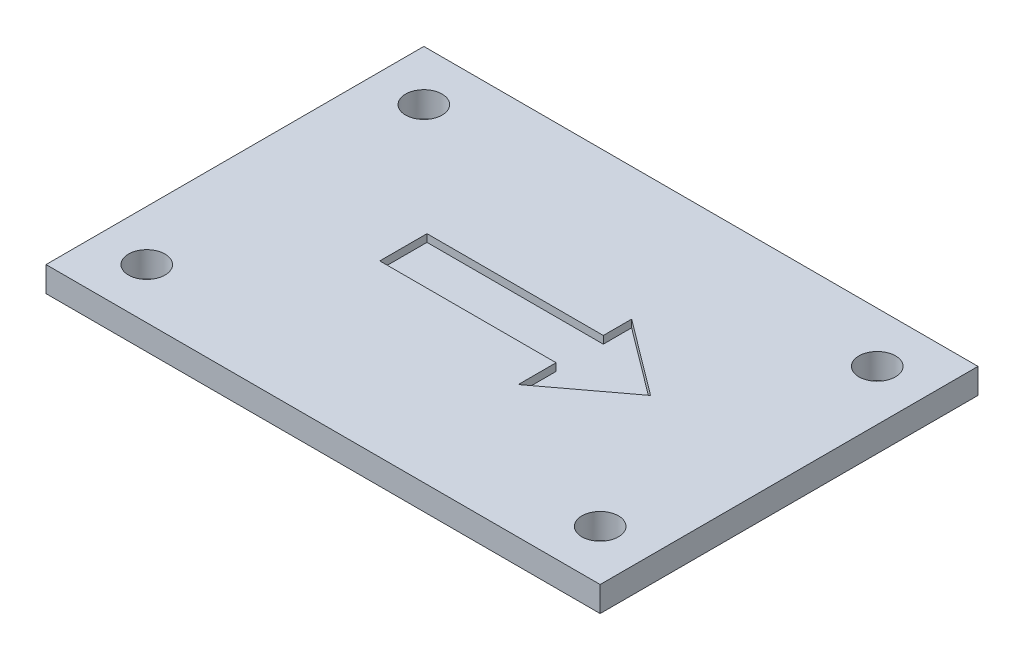
SolidWorks part; units mm, degrees
ref_plane "Front Plane" through (0, 0, 0) normal (0, 0, 1) x (1, 0, 0)
ref_plane "Top Plane" through (0, 0, 0) normal (0, 1, 0) x (1, 0, 0)
ref_plane "Right Plane" through (0, 0, 0) normal (1, 0, 0) x (0, 0, -1)
sketch "Sketch1" plane through (0, 0, 0) normal (0, 1, 0) x (1, 0, 0)
  line L1 (-22, -15) -> (22, -15)
  line L2 (-22, -15) -> (-22, 15)
  line L3 (-22, 15) -> (22, 15)
  line L4 (22, -15) -> (22, 15)
  line L5 (-22, -15) -> (22, 15) construction
  line L6 (-22, 15) -> (22, -15) construction
  point P0 (0, 0)
  dimension "D1" = 44
  dimension "D2" = 30
extrude "Lid Plate" add sketch "Sketch1" along normal blind 2
ref_plane "Lid Top" through (0, 2, 0) normal (0, 1, 0) x (1, 0, 0)
sketch "Sketch2" plane through (0, 2, 0) normal (0, 1, 0) x (1, 0, 0)
  circle A0 centre (-18, -11) radius 1.45
  circle A1 centre (-18, 11) radius 1.45
  circle A2 centre (18, -11) radius 1.45
  circle A3 centre (18, 11) radius 1.45
extrude "Clearance Holes" cut sketch "Sketch2" against normal blind 3
sketch "Sketch3" plane through (0, 2, 0) normal (0, 1, 0) x (1, 0, 0)
  line L0 (-9, -1.5) -> (5, -1.5)
  line L1 (5, -1.5) -> (5, -4.5)
  line L2 (5, -4.5) -> (11, 0)
  line L3 (-44.2539, 0) -> (44.2539, 0) construction
  line L4 (11, 0) -> (5, 4.5)
  line L5 (5, 4.5) -> (5, 2.25)
  line L6 (5, 2.25) -> (-9, 2.25)
  line L7 (-9, 2.25) -> (-9, -1.5)
extrude "Forward Arrow (+X)" cut sketch "Sketch3" against normal blind 0.6
sketch "Sketch4" plane through (0, 0, 0) normal (0, 1, 0) x (1, 0, 0)
  line L1 (-6, -6) -> (6, -6)
  line L2 (-6, -6) -> (-6, -8)
  line L3 (-6, -8) -> (6, -8)
  line L4 (6, -6) -> (6, -8)
extrude "Board Hold-Down Rib" add sketch "Sketch4" against normal blind 2.4
equation "\"PodL\"= 44.0"
equation "\"PodW\"= 30.0"
equation "\"LidT\"= 2.0"
equation "\"LidInset\"= 4.0"
equation "\"ClearD\"= 2.9"
equation "\"EngraveD\"= 0.6"
equation "\"D1@Sketch1\" = \"PodL\""
equation "\"D2@Sketch1\" = \"PodW\""
equation "\"D1@Lid Plate\" = \"LidT\""
equation "\"D1@Lid Top\" = \"LidT\""
equation "\"D1@Forward Arrow (+X)\" = \"EngraveD\""
